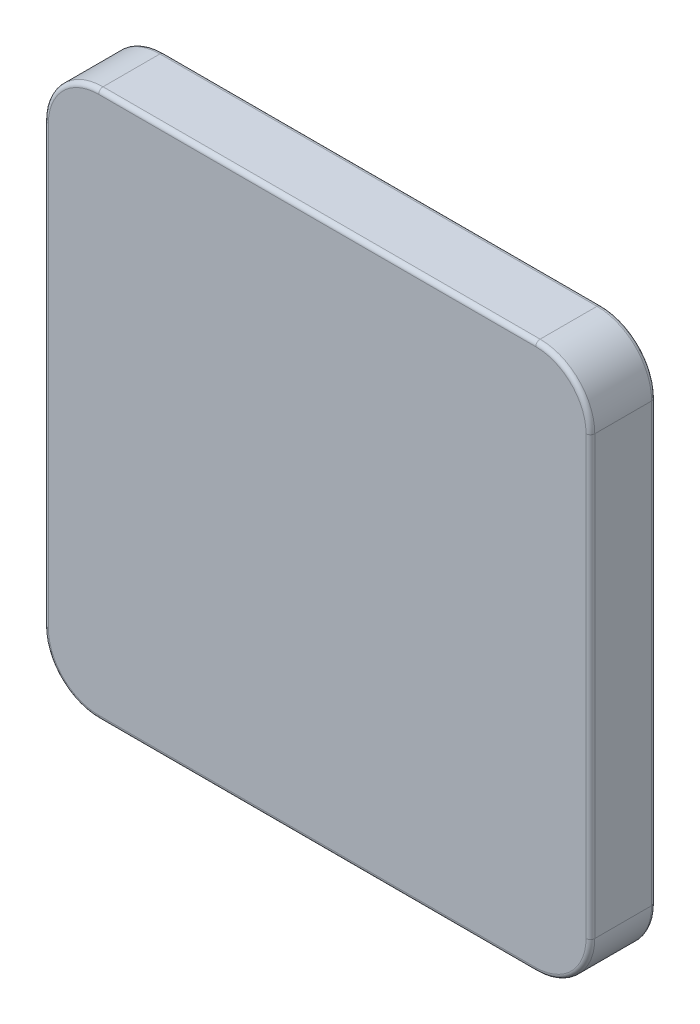
SolidWorks part; units mm, degrees
ref_plane "Front Plane" through (0, 0, 0) normal (0, 0, 1) x (1, 0, 0)
ref_plane "Top Plane" through (0, 0, 0) normal (0, 1, 0) x (1, 0, 0)
ref_plane "Right Plane" through (0, 0, 0) normal (1, 0, 0) x (0, 0, -1)
sketch "Sketch1" plane through (0, 0, 0) normal (0, 0, 1) x (1, 0, 0)
  line L1 (-1016, 1270) -> (1016, 1270)
  line L2 (-1270, 1016) -> (-1270, -1016)
  line L3 (-1016, -1270) -> (1016, -1270)
  line L4 (1270, 1016) -> (1270, -1016)
  line L5 (-1270, 1270) -> (1270, -1270) construction
  line L6 (-1270, -1270) -> (1270, 1270) construction
  arc A0 (-1270, 1016) -> (-1016, 1270) centre (-1016, 1016) cw
  arc A1 (-1016, -1270) -> (-1270, -1016) centre (-1016, -1016) cw
  arc A2 (1016, -1270) -> (1270, -1016) centre (1016, -1016) ccw
  arc A3 (1270, 1016) -> (1016, 1270) centre (1016, 1016) ccw
  point P0 (0, 0)
  dimension "D3" = 254
  dimension "D4" = 254
  dimension "D5" = 254
  dimension "D6" = 254
  dimension "D1" = 2540
  dimension "D2" = 2540
extrude "Boss-Extrude1" add sketch "Sketch1" along normal blind 304.8
fillet "Fillet2" radius 20.32 8 edges at (0, 1270, 304.8) (1195.6051, 1195.6051, 304.8) (1270, 0, 304.8) (1195.6051, -1195.6051, 304.8) (0, -1270, 304.8) (-1195.6051, -1195.6051, 304.8) (-1270, 0, 304.8) (-1195.6051, 1195.6051, 304.8)
fillet "Fillet3" radius 20.32 8 edges at (-1270, 0, 0) (-1195.6051, -1195.6051, 0) (0, -1270, 0) (1195.6051, -1195.6051, 0) (1270, 0, 0) (1195.6051, 1195.6051, 0) (0, 1270, 0) (-1195.6051, 1195.6051, 0)
